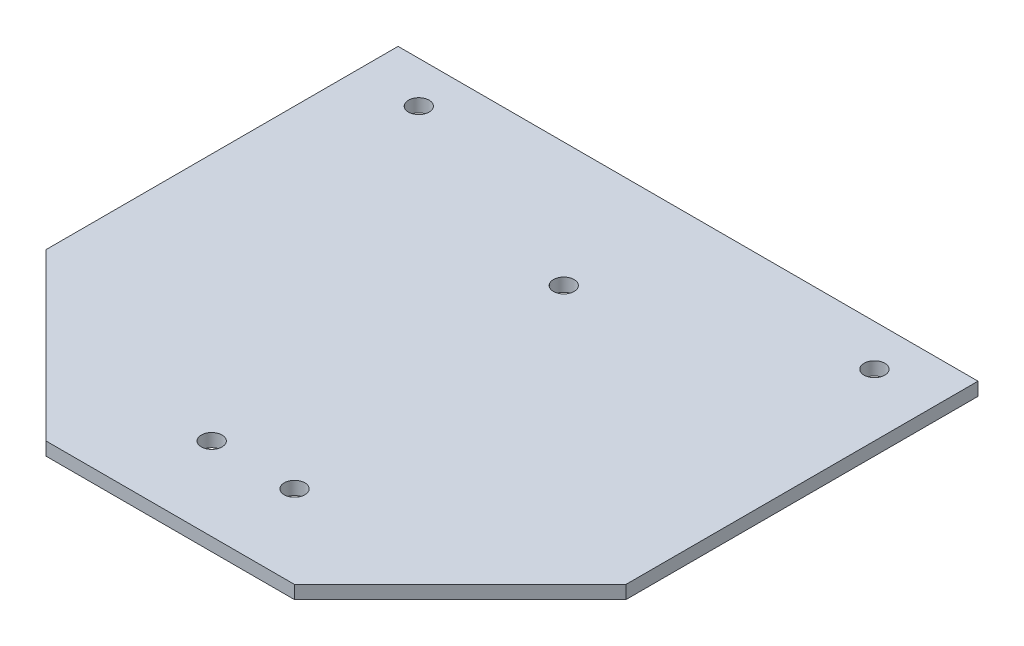
SolidWorks part; units mm, degrees
ref_plane "Front Plane" through (0, 0, 0) normal (0, 0, 1) x (1, 0, 0)
ref_plane "Top Plane" through (0, 0, 0) normal (0, 1, 0) x (1, 0, 0)
ref_plane "Right Plane" through (0, 0, 0) normal (1, 0, 0) x (0, 0, -1)
sketch "Sketch1" plane through (0, 0, 0) normal (0, 1, 0) x (1, 0, 0)
  line L0 (0, 0) -> (40, 0)
  line L1 (40, 0) -> (90, 0)
  line L2 (90, 125) -> (90, 85)
  line L3 (90, 125) -> (-50, 125)
  line L4 (-50, 125) -> (-50, 0)
  line L5 (90, 85) -> (90, 40)
  line L6 (90, 40) -> (90, 0)
  line L7 (90, 40) -> (-50, 40) construction
  line L8 (90, 85) -> (-50, 85) construction
  line L9 (30, 0) -> (30, 40) construction
  line L10 (10, 40) -> (10, 0) construction
  line L11 (90, 115) -> (-50, 115) construction
  line L12 (90, 95) -> (-50, 95) construction
  line L13 (-50, 0) -> (0, 0)
  circle A0 centre (-35, 115) radius 2.5
  circle A1 centre (75, 115) radius 2.5
  circle A2 centre (20, 95) radius 2.5
  circle A3 centre (10, 20) radius 2.5
  circle A4 centre (30, 20) radius 2.5
  dimension "D7" = 10
  dimension "D9" = 5
  dimension "D2" = 40
  dimension "D3" = 40
  dimension "D4" = 45
  dimension "D5" = 40
  dimension "D6" = 50
  dimension "D8" = 10
  dimension "D10" = 10
  dimension "D11" = 10
  dimension "D12" = 15
  dimension "D13" = 15
extrude "Boss-Extrude1" add sketch "Sketch1" along normal blind 3.18
sketch "Sketch3" plane through (0, 0, 0) normal (0, -1, 0) x (1, 0, 0)
  line L0 (90, -40) -> (50, 0)
  line L1 (90, 0) -> (90, -125) construction
  line L2 (-50, 0) -> (90, 0) construction
  line L3 (50, 0) -> (90, 0)
  line L4 (90, 0) -> (90, -40)
  line L5 (-50, 0) -> (-10, 0)
  line L6 (-50, 0) -> (90, 0) construction
  line L7 (-10, 0) -> (-50, -40)
  line L8 (-50, -125) -> (-50, 0) construction
  line L9 (-50, -40) -> (-50, 0)
  line L10 (90, -40) -> (-50, -40) construction
  dimension "D1" = 40
  dimension "D2" = 40
extrude "Cut-Extrude1" cut sketch "Sketch3" against normal through all
